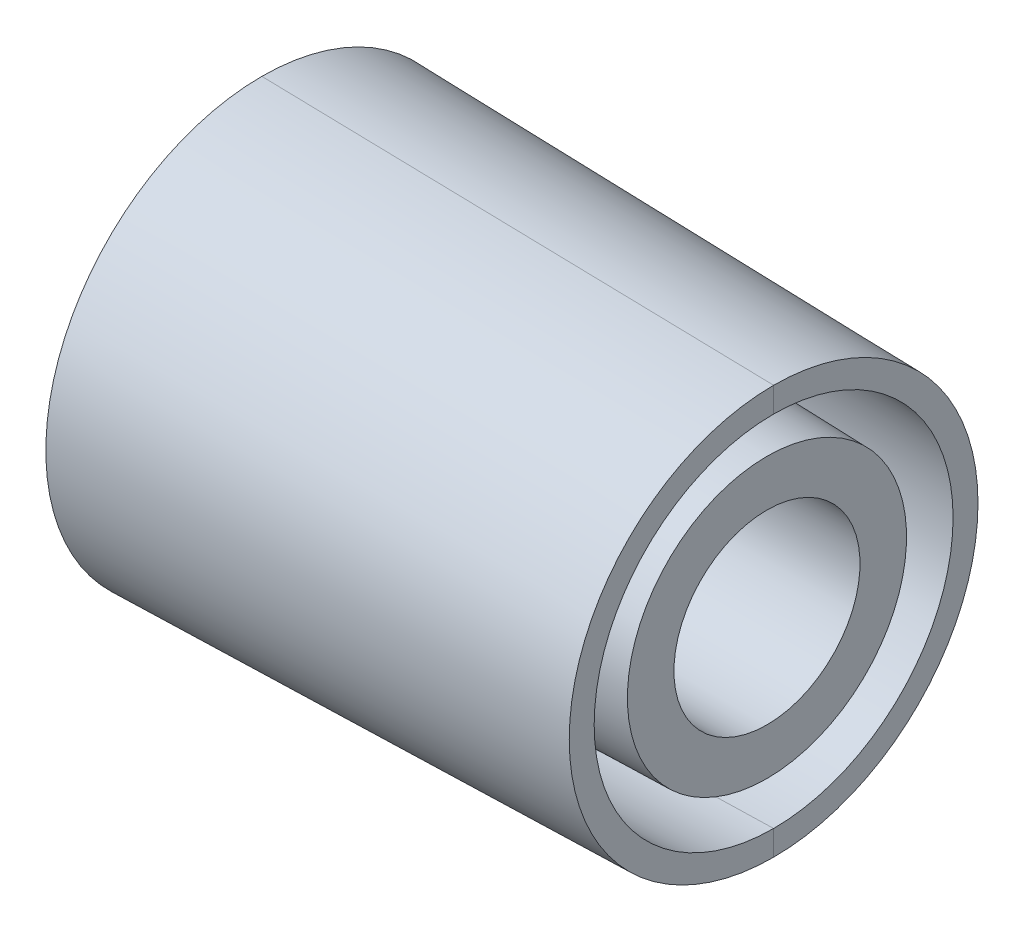
SolidWorks part; units mm, degrees
ref_plane "Front Plane" through (0, 0, 0) normal (0, 0, 1) x (1, 0, 0)
ref_plane "Top Plane" through (0, 0, 0) normal (0, 1, 0) x (1, 0, 0)
ref_plane "Right Plane" through (0, 0, 0) normal (1, 0, 0) x (0, 0, -1)
sketch "Sketch1" plane through (0, 0, 0) normal (0, 0, 1) x (1, 0, 0)
  line L0 (0, 0) -> (4000, 0) construction
  line L1 (1900, 280) -> (1900, 460)
  line L2 (1900, 460) -> (3400, 420)
  line L3 (3400, 420) -> (3400, 280)
  line L4 (3400, 280) -> (1900, 280)
revolve "Revolve1" add sketch "Sketch1" angle 360 about L0
sketch "Sketch2" plane through (0, 0, 0) normal (0, 0, 1) x (1, 0, 0)
  line L0 (0, 0) -> (4000, 0) construction
  line L1 (1880, 580) -> (1880, 650)
  line L2 (1880, 650) -> (3420, 615)
  line L3 (3420, 615) -> (3420, 540)
  line L4 (3420, 540) -> (1880, 580)
revolve "Revolve2" add sketch "Sketch2" angle 180 about L0
sketch "Sketch3" plane through (0, 0, 0) normal (0, 0, 1) x (1, 0, 0)
  line L0 (0, 0) -> (4000, 0) construction
  line L1 (1880, -580) -> (1880, -650)
  line L2 (1880, -650) -> (3420, -615)
  line L3 (3420, -615) -> (3420, 615) construction
  line L4 (3420, -615) -> (3420, -540)
  line L5 (3420, -540) -> (1880, -580)
revolve "Revolve3" add sketch "Sketch3" angle 180 about L0
